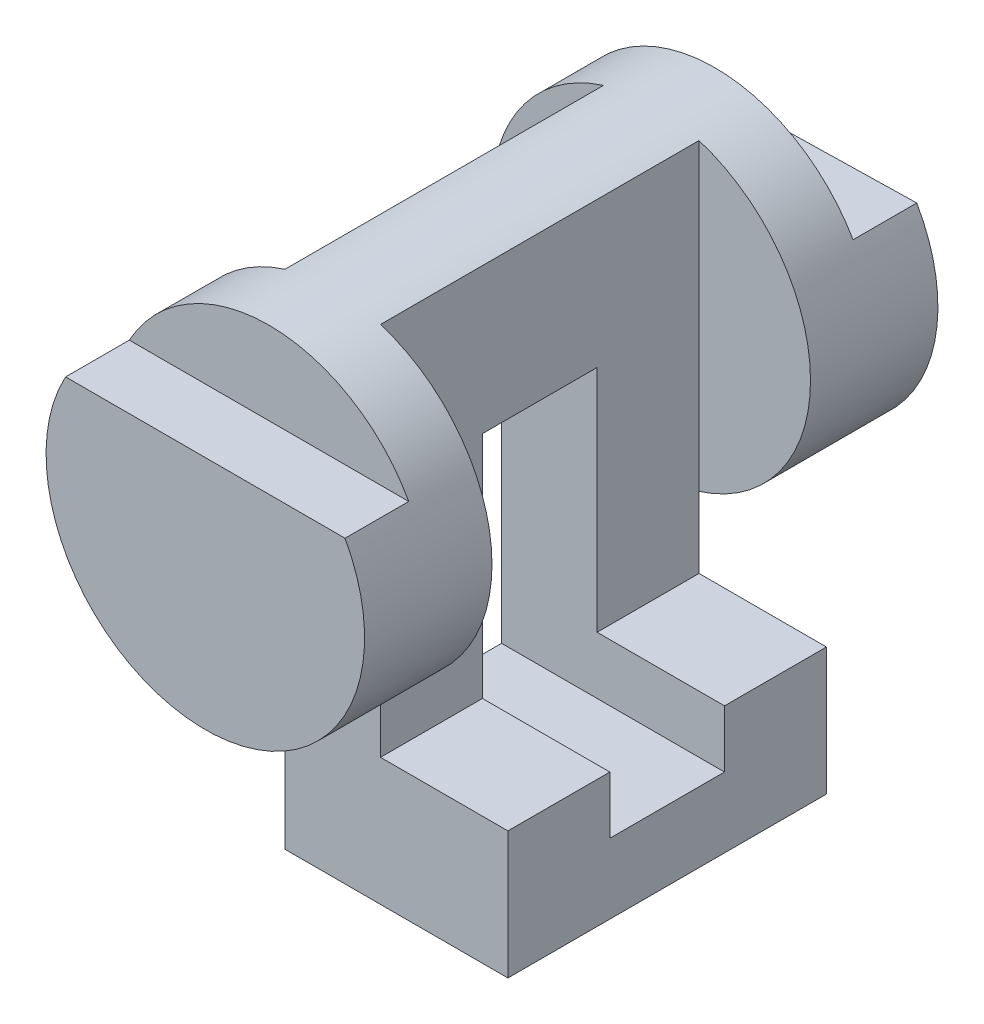
SolidWorks part; units mm, degrees
ref_plane "Front Plane" through (0, 0, 0) normal (0, 0, 1) x (1, 0, 0)
ref_plane "Top Plane" through (0, 0, 0) normal (0, 1, 0) x (1, 0, 0)
ref_plane "Right Plane" through (0, 0, 0) normal (1, 0, 0) x (0, 0, -1)
sketch "Sketch1" plane through (0, 0, 0) normal (1, 0, 0) x (0, 0, -1)
  line L0 (-22.6337, 0) -> (-22.6337, -20)
  line L1 (-22.6337, -20) -> (27.3663, -20)
  line L2 (27.3663, -20) -> (27.3663, 0)
  line L3 (27.3663, 0) -> (11.3663, 0)
  line L4 (11.3663, 0) -> (11.3663, -9)
  line L5 (11.3663, -9) -> (-6.6337, -9)
  line L6 (-6.6337, -9) -> (-6.6337, 0)
  line L7 (-6.6337, 0) -> (-22.6337, 0)
  dimension "D1" = 50
  dimension "D2" = 20
  dimension "D3" = 20
  dimension "D4" = 9
  dimension "D5" = 16
  dimension "D6" = 16
extrude "Boss-Extrude1" add sketch "Sketch1" against normal blind 20
sketch "Sketch2" plane through (0, 0, 22.6337) normal (0, 0, 1) x (1, 0, 0)
  line L0 (-20, 0) -> (-20, 54)
  line L1 (-20, 54) -> (-35, 54)
  line L2 (-35, 54) -> (-35, -20)
  line L3 (-35, -20) -> (-20, -20)
  line L4 (-20, 0) -> (-20, -20)
  line L5 (0, 0) -> (0, -20) construction
  dimension "D1" = 35
  dimension "D2" = 74
extrude "Boss-Extrude2" add sketch "Sketch2" against normal blind 50
sketch "Sketch3" plane through (-20, 0, 0) normal (1, 0, 0) x (0, 0, -1)
  line L0 (-6.6337, -9) -> (-6.6337, 36)
  line L1 (-6.6337, 36) -> (11.3663, 36)
  line L2 (-6.6337, -9) -> (11.3663, -9)
  line L3 (11.3663, -9) -> (11.3663, 36)
  point P8 (0, 0)
  dimension "D1" = 45
extrude "Cut-Extrude1" cut sketch "Sketch3" against normal blind 50
sketch "Sketch4" plane through (0, 0, 22.6337) normal (0, 0, 1) x (1, 0, 0)
  line L0 (-35, -20) -> (0, -20) construction
  circle A0 centre (-27.5, 35) radius 25
  dimension "D1" = 50
  dimension "D2" = 55
extrude "Boss-Extrude3" add sketch "Sketch4" along normal blind 20
sketch "Sketch5" plane through (0, 0, 42.6337) normal (0, 0, 1) x (1, 0, 0)
  line L0 (-49.4317, 47) -> (-5.5683, 47)
  circle A0 centre (-27.5, 35) radius 25 construction
  arc A1 (-49.4317, 47) -> (-5.5683, 47) centre (-27.5, 35) cw
  dimension "D1" = 12
extrude "Cut-Extrude2" cut sketch "Sketch5" against normal blind 10
sketch "Sketch6" plane through (0, 0, 22.6337) normal (0, 0, -1) x (-1, 0, 0)
  line L0 (20, 54) -> (20, 58.8485)
  line L1 (35, 54) -> (35, 58.8485)
  line L2 (20, 54) -> (35, 54)
  arc A0 (35, 11.1515) -> (20, 11.1515) centre (27.5, 35) ccw construction
  arc A1 (20, 58.8485) -> (35, 58.8485) centre (27.5, 35) cw
extrude "Boss-Extrude4" add sketch "Sketch6" along normal blind 50
sketch "Sketch7" plane through (0, 0, -27.3663) normal (0, 0, -1) x (-1, 0, 0)
  circle A0 centre (27.5, 35) radius 25
extrude "Boss-Extrude5" add sketch "Sketch7" along normal blind 20
sketch "Sketch8" plane through (0, 0, -47.3663) normal (0, 0, -1) x (-1, 0, 0)
  line L2 (5.8207, 47.4503) -> (49.6748, 46.5446)
  circle A0 centre (27.5, 35) radius 25 construction
  arc A4 (5.8207, 47.4503) -> (49.6748, 46.5446) centre (27.5, 35) cw
  dimension "D1" = 12
extrude "Cut-Extrude3" cut sketch "Sketch8" against normal blind 10
